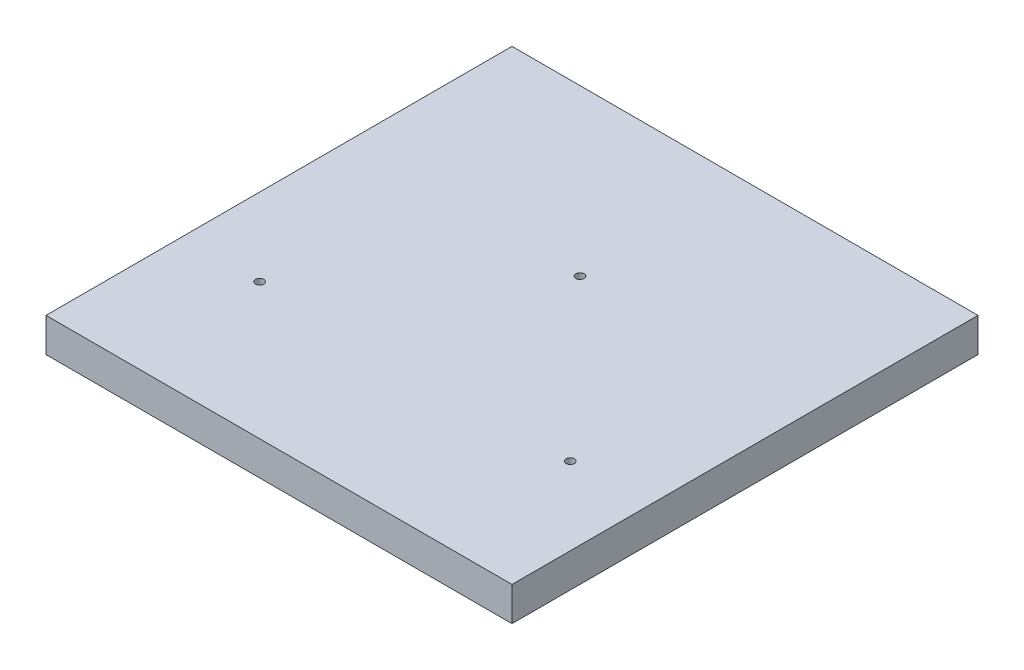
SolidWorks part; units mm, degrees
ref_plane "Front Plane" through (0, 0, 0) normal (0, 0, 1) x (1, 0, 0)
ref_plane "Top Plane" through (0, 0, 0) normal (0, 1, 0) x (1, 0, 0)
ref_plane "Right Plane" through (0, 0, 0) normal (1, 0, 0) x (0, 0, -1)
sketch "Sketch1" plane through (0, 0, 0) normal (0, 0, 1) x (1, 0, 0)
  line L7 (-76.2, -5.5563) -> (76.2, -5.5563)
  line L8 (-76.2, -5.5563) -> (-76.2, 5.5562)
  line L9 (-76.2, 5.5562) -> (76.2, 5.5562)
  line L10 (76.2, -5.5563) -> (76.2, 5.5562)
  line L11 (-76.2, -5.5563) -> (76.2, 5.5562) construction
  line L12 (-76.2, 5.5562) -> (76.2, -5.5563) construction
  point P4 (0, 0)
  point P14 (0, 0)
  dimension "Thickness" = 11.1125
  dimension "Width" = 152.4
sketch "Sketch2" plane through (0, 0, 0) normal (0, 1, 0) x (0, 0, -1)
  line L0 (76.2, 76.2) -> (-76.2, 76.2) construction
  point P4 (0, 76.2)
  dimension "Length" = 152.4
sketch "Sketch3" plane through (0, 0, 0) normal (0, 0, 1) x (1, 0, 0)
  line L6 (-76.2, 5.5562) -> (76.2, 5.5562)
  line L7 (76.2, 5.5562) -> (76.2, -5.5563)
  line L8 (76.2, -5.5563) -> (-76.2, -5.5563)
  line L9 (-76.2, -5.5563) -> (-76.2, 5.5562)
extrude "Boss-Extrude1" add sketch "Sketch3" along normal mid plane 152.4
sketch "Sketch4" plane through (0, 5.5562, 0) normal (0, 1, 0) x (1, 0, 0)
  point P0 (0, 22.2235)
  point P1 (50.8, -31.75)
  point P3 (-50.8, -31.75)
hole_wizard "#6-32 Tapped Hole1" positions "Sketch4" profile "Sketch5" tap size "#6-32" standard "ANSI Inch" end condition through all
sketch "Sketch5" plane through (0, 5.5562, -22.2235) normal (1, 0, 0) x (0, 0, 1)
  line L0 (0, 0) -> (0, 11.1125)
  line L1 (0, 11.1125) -> (1.3525, 11.1125)
  line L2 (1.3525, 11.1125) -> (1.3525, 0)
  line L5 (1.3525, 0) -> (0, 0)
  line L11 (0, -6.35) -> (0, 107.95) construction
  dimension "Thru Tap Drill Dia." = 2.7051
  dimension "Thru Tap Drill Depth" = 11.1125
cosmetic thread "Hole Thread1"
cosmetic thread "Hole Thread2"
cosmetic thread "Hole Thread3"
equation "\"D1@Boss-Extrude1\" = \"Length@Sketch2\""
